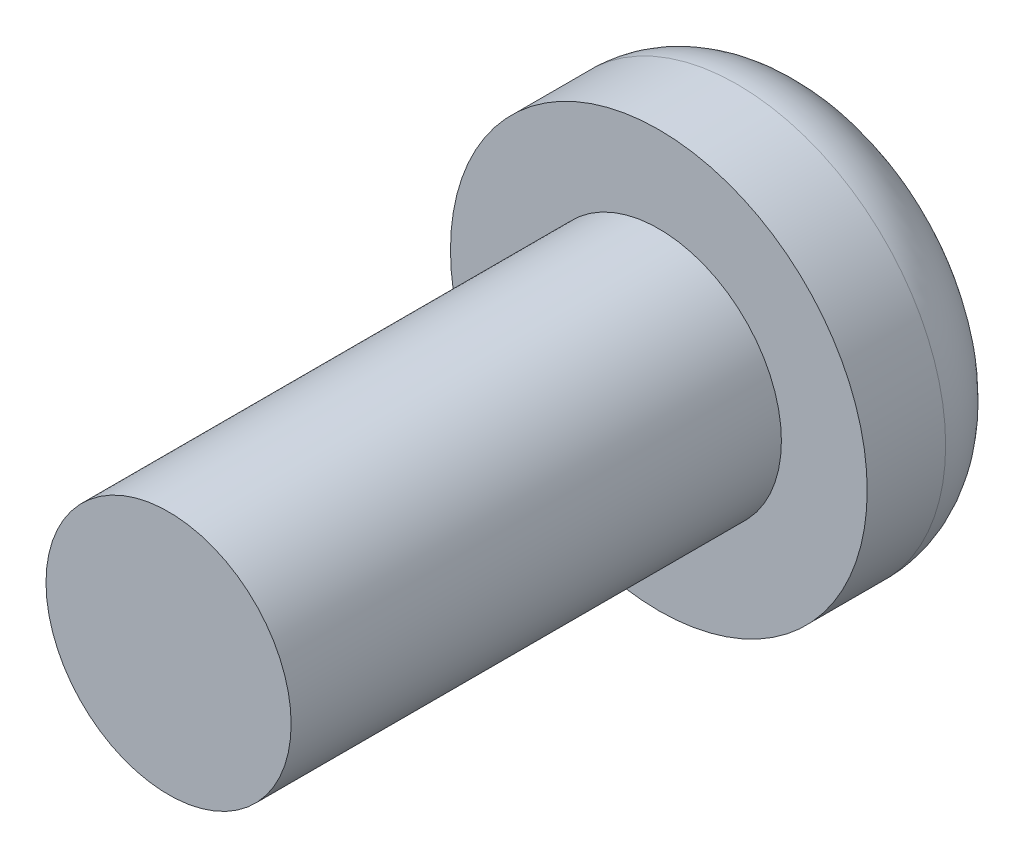
SolidWorks part; units mm, degrees
ref_plane "Front Plane" through (0, 0, 0) normal (0, 0, 1) x (1, 0, 0)
ref_plane "Top Plane" through (0, 0, 0) normal (0, 1, 0) x (1, 0, 0)
ref_plane "Right Plane" through (0, 0, 0) normal (1, 0, 0) x (0, 0, -1)
sketch "Sketch1" plane through (0, 0, 0) normal (0, 0, 1) x (1, 0, 0)
  circle A0 centre (0, 0) radius 4.25
  dimension "D2" = 8.5
extrude "Boss-Extrude4" add sketch "Sketch1" along normal blind 3.2
sketch "Sketch2" plane through (0, 0, 0) normal (0, 1, 0) x (1, 0, 0)
  line L0 (4.25, 0) -> (-4.25, 0) construction
  line L1 (-4.25, 0) -> (-4.25, -3.2) construction
  line L3 (-4.25, -1.6) -> (-4.25, 0)
  line L4 (-4.25, 0) -> (-2.65, 0)
  line L7 (0, 0) -> (0, -3.2) construction
  line L8 (-4.25, -3.2) -> (4.25, -3.2) construction
  arc A0 (-2.65, 0) -> (-4.25, -1.6) centre (-2.65, -1.6) ccw
  dimension "D1" = 1.6
revolve "Cut-Revolve1" cut sketch "Sketch2" angle 360 about L7
sketch "Sketch3" plane through (0, 0, 0) normal (0, 0, -1) x (-1, 0, 0)
  line L0 (1.76, 0) -> (-1.76, 0) construction
  line L1 (-0.5, 2) -> (0.5, 2)
  line L2 (-0.5, 2) -> (-0.5, -2)
  line L3 (-0.5, -2) -> (0.5, -2)
  line L4 (0.5, 2) -> (0.5, -2)
  line L5 (-2, 0.5) -> (2, 0.5)
  line L6 (-2, 0.5) -> (-2, -0.5)
  line L7 (-2, -0.5) -> (2, -0.5)
  line L8 (2, 0.5) -> (2, -0.5)
  line L9 (0, 0) -> (0, 1.2144) construction
  dimension "D1" = 4
  dimension "D2" = 4
  dimension "D3" = 1
  dimension "D4" = 1
  dimension "D5" = 0.5
  dimension "D6" = 1.5
  dimension "D7" = 0.5
  dimension "D8" = 2
extrude "Cut-Extrude1" cut sketch "Sketch3" against normal blind 0.5
sketch "Sketch4" plane through (0, 0, 3.2) normal (0, 0, 1) x (1, 0, 0)
  circle A0 centre (0, 0) radius 2.5
  dimension "D1" = 5
extrude "Boss-Extrude7" add sketch "Sketch4" along normal blind 10 contours A0
